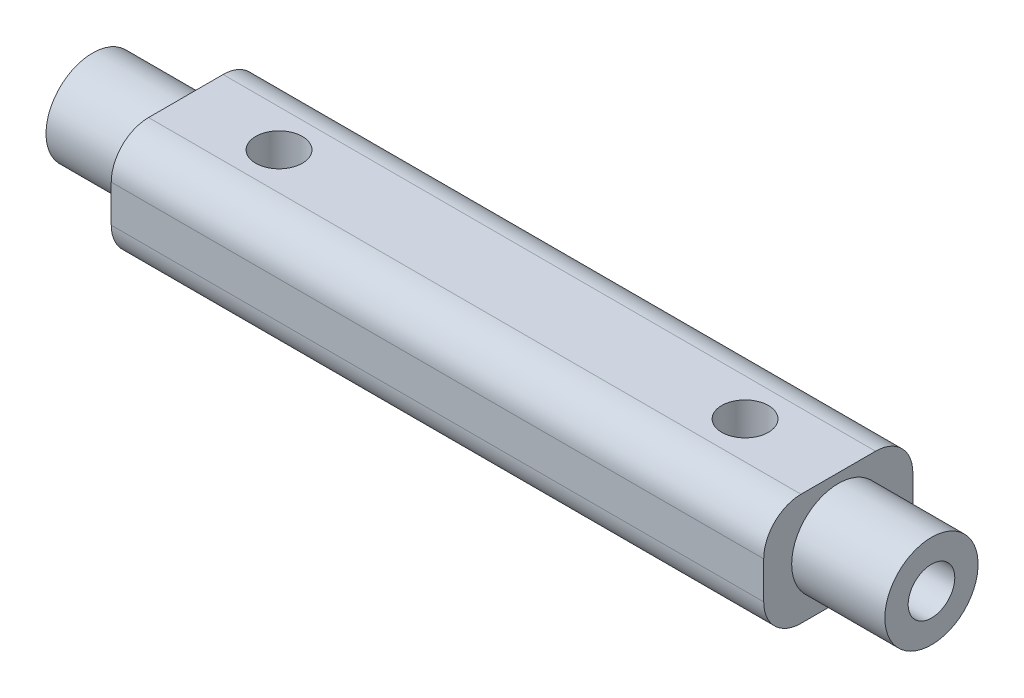
SolidWorks part; units mm, degrees
ref_plane "前基準面" through (0, 0, 0) normal (0, 0, 1) x (1, 0, 0)
ref_plane "上基準面" through (0, 0, 0) normal (0, 1, 0) x (1, 0, 0)
ref_plane "右基準面" through (0, 0, 0) normal (1, 0, 0) x (0, 0, -1)
sketch "草圖1" plane through (0, 0, 0) normal (1, 0, 0) x (0, 0, -1)
  line L0 (4, -3) -> (-4, 3) construction
  line L1 (-4, 3) -> (4, 3)
  line L2 (-4, 3) -> (-4, -3)
  line L3 (-4, -3) -> (4, -3)
  line L4 (4, 3) -> (4, -3)
  dimension "D1" = 6
  dimension "D2" = 8
extrude "填料-伸長1" add sketch "草圖1" along normal mid plane 35
sketch "草圖2" plane through (0, 0, 0) normal (1, 0, 0) x (0, 0, -1)
  circle A0 centre (0, 0) radius 2.5
  dimension "D1" = 5
extrude "填料-伸長2" add sketch "草圖2" along normal mid plane 45
fillet "圓角1" radius 2 4 edges at (0, -3, -4) (0, 3, -4) (0, -3, 4) (0, 3, 4)
hole_wizard "M3 螺紋孔1" positions "草圖4" profile "草圖5" tap size "M3" standard "Iso" end condition through all
sketch "草圖4" plane through (22.5, 0, 0) normal (1, 0, 0) x (0, 0, -1)
  point P0 (0, 0)
sketch "草圖5" plane through (22.5, 0, 0) normal (0, 1, 0) x (0, 0, -1)
  line L0 (0, 0) -> (0, 45)
  line L1 (0, 45) -> (1.25, 45)
  line L2 (1.25, 45) -> (1.25, 0)
  line L5 (1.25, 0) -> (0, 0)
  line L11 (0, -6.35) -> (0, 107.95) construction
  dimension "貫穿螺孔鑽直徑" = 2.5
  dimension "貫穿螺孔鑽深度" = 45
cosmetic thread "鑽孔螺紋1" parameters "D2"=3
sketch "草圖6" plane through (0, 3, 0) normal (0, 1, 0) x (1, 0, 0)
  line L0 (-12.5, 0) -> (12.5, 0) construction
  circle A0 centre (-12.5, 0) radius 1
  circle A1 centre (12.5, 0) radius 1
  dimension "D2" = 2
  dimension "D3" = 2
  dimension "D1" = 25
extrude "除料-伸長1" cut sketch "草圖6" against normal through all
hole_wizard "M3 螺紋孔2" positions "3D草圖1" profile "草圖8" tap size "M3" standard "Iso" end condition through all
sketch3d "3D草圖1"
  line L0 (-12.5, 0.75, 0) -> (-12.5, 3, 0) construction
  line L1 (12.5, 0.75, 0) -> (12.5, 3, 0) construction
  point P0 (-12.5, 3, 0)
  point P4 (12.5, 3, 0)
sketch "草圖8" plane through (-12.5, 3, 0) normal (1, 0, 0) x (0, 0, 1)
  line L0 (0, 0) -> (0, 6)
  line L1 (0, 6) -> (1.25, 6)
  line L2 (1.25, 6) -> (1.25, 0)
  line L5 (1.25, 0) -> (0, 0)
  line L11 (0, -6.35) -> (0, 107.95) construction
  dimension "貫穿螺孔鑽直徑" = 2.5
  dimension "貫穿螺孔鑽深度" = 6
cosmetic thread "鑽孔螺紋2" parameters "D2"=3
cosmetic thread "鑽孔螺紋3" parameters "D2"=3
